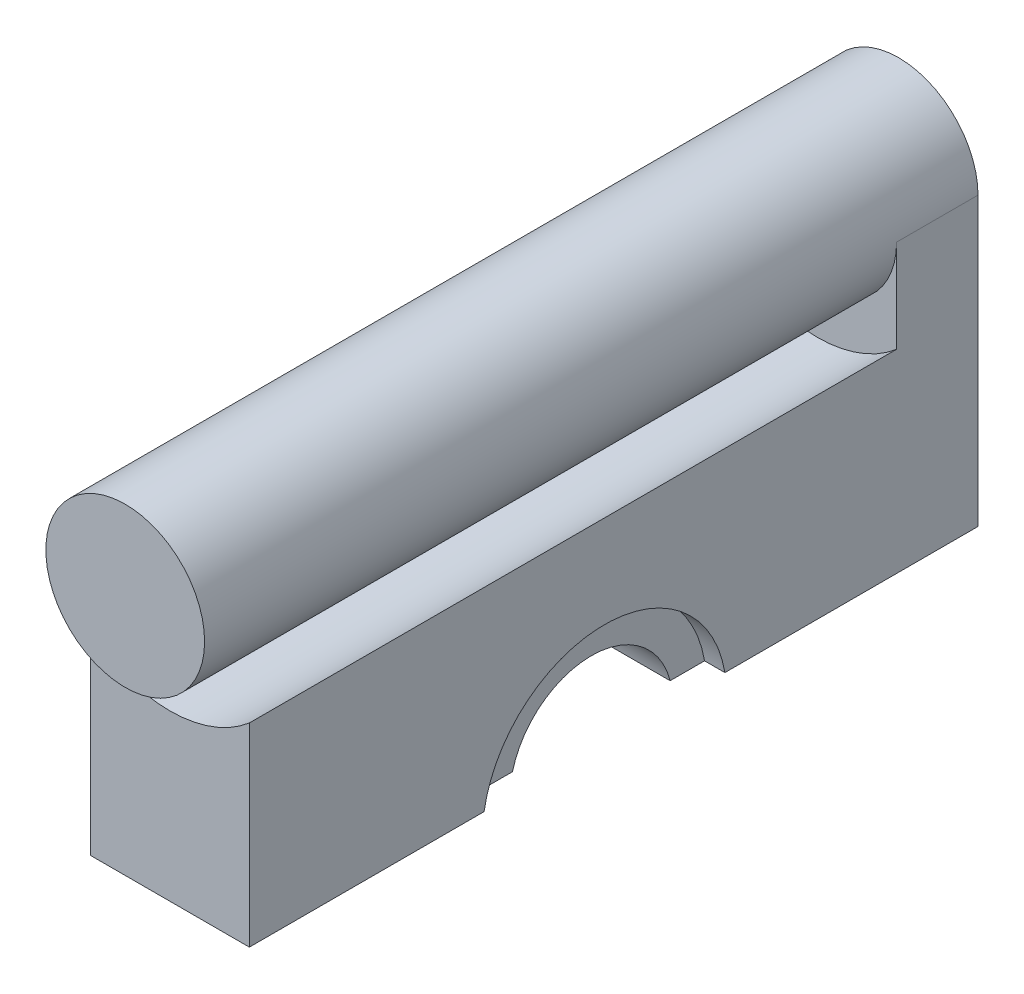
SolidWorks part; units mm, degrees
ref_plane "정면" through (0, 0, 0) normal (0, 0, 1) x (1, 0, 0)
ref_plane "윗면" through (0, 0, 0) normal (0, 1, 0) x (1, 0, 0)
ref_plane "우측면" through (0, 0, 0) normal (1, 0, 0) x (0, 0, -1)
sketch "스케치1" plane through (0, 0, 0) normal (0, 0, 1) x (1, 0, 0)
  circle A0 centre (0, 0) radius 1.95
  dimension "D1" = 3.9
extrude "보스-돌출1" add sketch "스케치1" along normal blind 19
sketch "스케치4" plane through (0, 0, 0) normal (1, 0, 0) x (0, 0, -1)
  line L5 (-2, 1.95) -> (0, 1.95)
  line L6 (-2, 1.95) -> (-2, -7.05)
  line L7 (-2, -7.05) -> (0, -7.05)
  line L8 (0, 1.95) -> (0, -7.05)
  line L9 (-2, 1.95) -> (0, -7.05) construction
  line L10 (-2, -7.05) -> (0, 1.95) construction
  point P0 (-1, -2.55)
  dimension "D1" = 2
  dimension "D2" = 9
extrude "보스-돌출2" add sketch "스케치4" along normal mid plane 3.9
sketch "스케치5" plane through (0, 0, 19) normal (0, 0, 1) x (1, 0, 0)
  line L0 (-1.95, 0) -> (-1.95, 1.95)
  line L1 (-1.95, 0) -> (-1.95, -7.05) construction
  line L2 (-1.95, 1.95) -> (1.95, 1.95)
  line L3 (1.95, 1.95) -> (1.95, 0)
  line L4 (1.95, 1.95) -> (1.95, 0) construction
  line L5 (1.95, 0) -> (1.95, 1.95)
  circle A0 centre (0, 0) radius 1.95 construction
  circle A1 centre (0, 0) radius 1.95
  circle M1 centre (0, 0) radius 1.95
extrude "컷-돌출1" cut sketch "스케치5" against normal through all contours L2 L0 M1 | L3 L2 M1
sketch "스케치8" plane through (0, 0, 2) normal (0, 0, 1) x (1, 0, 0)
  line L0 (-1.95, 0) -> (-1.95, -7.05)
  line L1 (-1.95, -7.05) -> (1.95, -7.05)
  line L2 (1.95, -7.05) -> (1.95, 0)
  line L3 (-1.95, -2.2798) -> (-1.95, -7.05)
  line L4 (1.95, -7.05) -> (1.95, -2.2798)
  line L6 (-1.95, 0) -> (-1.95, -7.05) construction
  circle A0 centre (0, 0) radius 1.95 construction
  circle A2 centre (0, 0) radius 1.95
  circle A3 centre (0, 0) radius 1.95
  arc A4 (-1.95, -2.2798) -> (1.95, -2.2798) centre (0, 0) ccw
  line M2 (1.95, -7.05) -> (1.95, 0)
  line M5 (-1.95, -7.05) -> (1.95, -7.05)
  dimension "D2" = 6
  dimension "D1" = 0
extrude "보스-돌출4" add sketch "스케치8" along normal blind 15.9 contours A4 L0 M5 M2
sketch "스케치9" plane through (-1.95, 0, 0) normal (-1, 0, 0) x (0, 0, 1)
  line L2 (19, -1.95) -> (19, 1.95) construction
  line L5 (17.9, -7.05) -> (0, -7.05) construction
  circle A0 centre (9, -7.55) radius 2
  dimension "D1" = 4
  dimension "D2" = 10
  dimension "D3" = 0.5
extrude "컷-돌출2" cut sketch "스케치9" against normal blind 17
sketch "스케치11" plane through (1.95, 0, 0) normal (1, 0, 0) x (0, 0, -1)
  line L0 (-7.0635, -7.05) -> (0, -7.05) construction
  line L1 (0, -7.05) -> (0, 0) construction
  circle A0 centre (-9.1761, -7.55) radius 3
  dimension "D1" = 0.5
  dimension "D3" = 6
  dimension "D2" = 9.1761
extrude "컷-돌출4" cut sketch "스케치11" against normal blind 0.5
equation "\"15.9.00mm\"=16"
